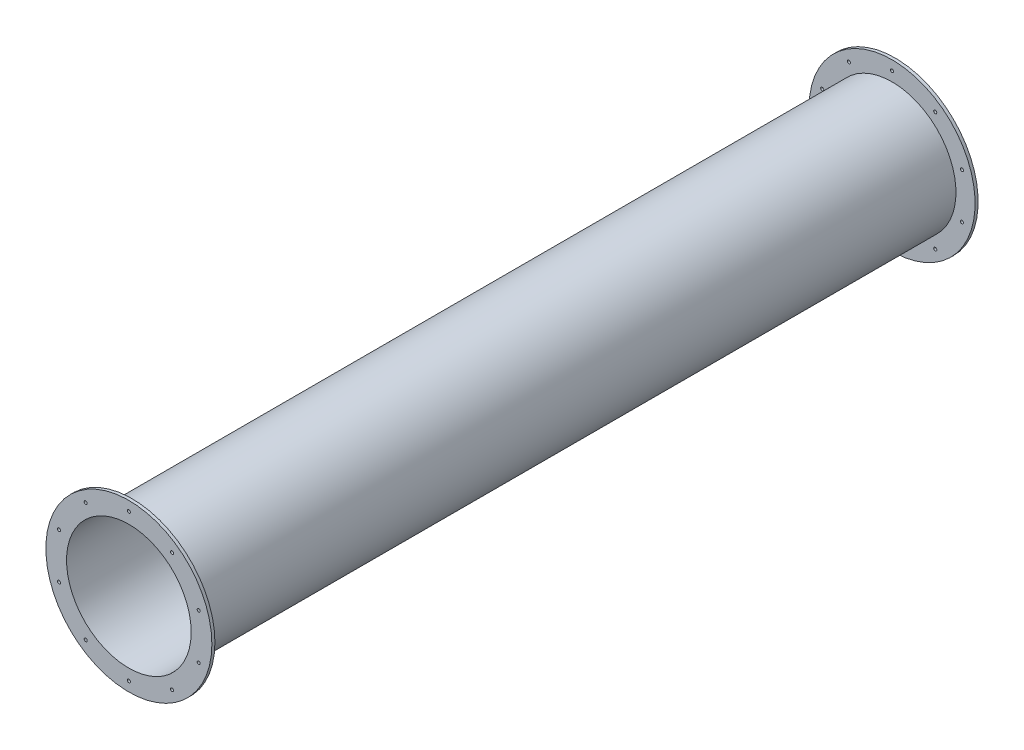
SolidWorks part; units mm, degrees
ref_plane "Front Plane" through (0, 0, 0) normal (0, 0, 1) x (1, 0, 0)
ref_plane "Top Plane" through (0, 0, 0) normal (0, 1, 0) x (1, 0, 0)
ref_plane "Right Plane" through (0, 0, 0) normal (1, 0, 0) x (0, 0, -1)
sketch "Sketch1" plane through (0, 0, 0) normal (0, 0, 1) x (1, 0, 0)
  circle A0 centre (0, 0) radius 250
  circle A1 centre (0, 0) radius 244
  dimension "D1" = 500
  dimension "D2" = 6
extrude "Boss-Extrude1" add sketch "Sketch1" along normal blind 3000
sketch "Sketch2" plane through (0, 0, 3000) normal (0, 0, 1) x (1, 0, 0)
  circle A0 centre (0, 0) radius 250
  circle A1 centre (0, 0) radius 250 construction
  circle A2 centre (0, 0) radius 325
  dimension "D1" = 650
extrude "Boss-Extrude2" add sketch "Sketch2" against normal blind 12
sketch "Sketch4" plane through (0, 0, 0) normal (0, 0, -1) x (-1, 0, 0)
  circle A0 centre (0, 0) radius 250
  circle A1 centre (0, 0) radius 250 construction
  circle A2 centre (0, 0) radius 325
  circle A3 centre (0, 0) radius 325 construction
extrude "Boss-Extrude3" add sketch "Sketch4" against normal blind 12
sketch "Sketch6" plane through (0, 0, 3000) normal (0, 0, 1) x (1, 0, 0)
  circle A0 centre (0, 0) radius 287.5 construction
  circle A1 centre (0, 287.5) radius 6
  circle A2 centre (168.9883, 232.5924) radius 6
  circle A3 centre (273.4287, 88.8424) radius 6
  circle A4 centre (273.4287, -88.8424) radius 6
  circle A5 centre (168.9883, -232.5924) radius 6
  circle A6 centre (0, -287.5) radius 6
  circle A7 centre (-168.9883, -232.5924) radius 6
  circle A8 centre (-273.4287, -88.8424) radius 6
  circle A9 centre (-273.4287, 88.8424) radius 6
  circle A10 centre (-168.9883, 232.5924) radius 6
  point P25 (0, 0)
  dimension "D1" = 575
  dimension "D2" = 12
extrude "Cut-Extrude3" cut sketch "Sketch6" against normal through all
equation "\"mbtOD\" = 500"
equation "\"mbtT\" = 6"
equation "\"mbtL\" = 3000"
equation "\"mbtFlangeOD\" = 650"
equation "\"mbtFlangeT\" = 12"
equation "\"mbtFlangeHoleDia\" = 12"
equation "\"D1@Boss-Extrude1\"=\"mbtL\""
equation "\"D1@Boss-Extrude2\"=\"mbtFlangeT\""
equation "\"D1@Boss-Extrude3\"=\"mbtFlangeT\""
equation "\"D1@Sketch1\"=\"mbtOD\""
equation "\"D2@Sketch1\"=\"mbtT\""
equation "\"D1@Sketch2\"=\"mbtFlangeOD\""
equation "\"D1@Sketch6\"=(\"mbtOD\"+\"mbtFlangeOD\")/2"
equation "\"D2@Sketch6\"=\"mbtFlangeHoleDia\""
equation "\"mbtOringSize\" = 10 "
equation "\"mbtOringDia\" = 620"
equation "\"mbtFlangeBoltCircleDia\" = 650"
equation "\"mbtWidth\" = 2250"
equation "\"skiWidth\" = 1250"
